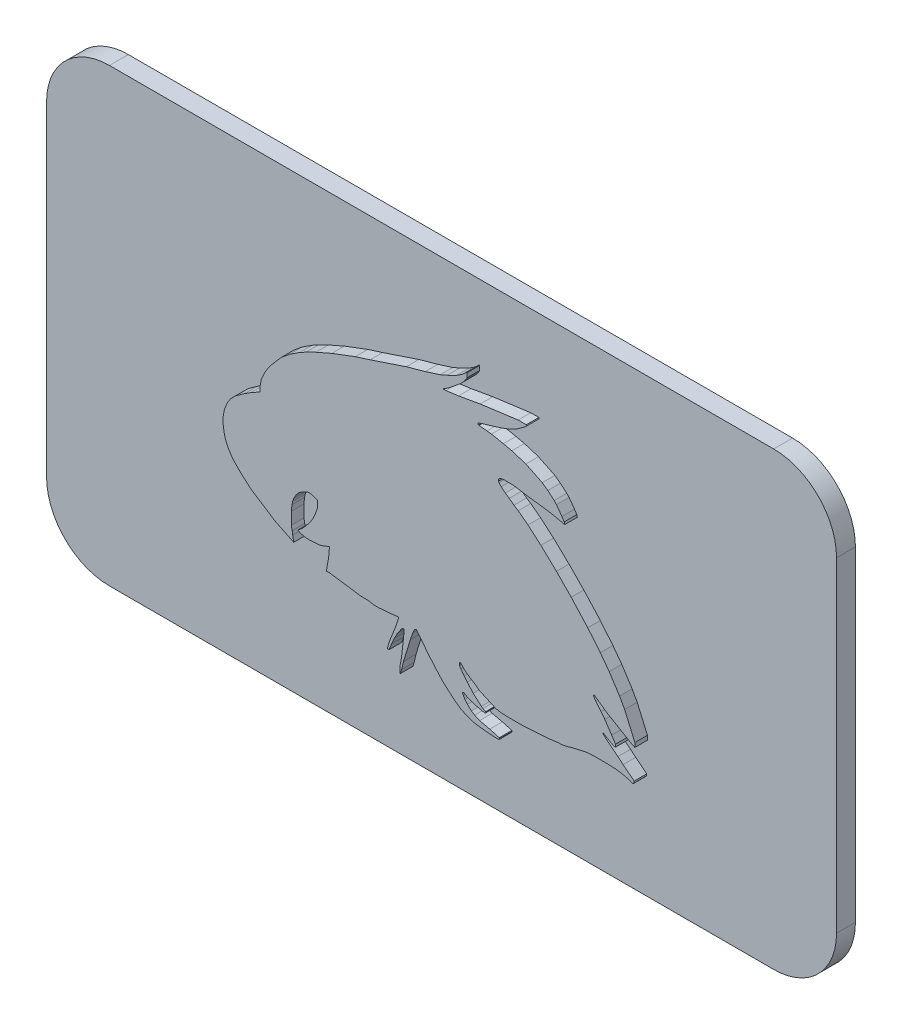
SolidWorks part; units mm, degrees
ref_plane "Alzado" through (0, 0, 0) normal (0, 0, 1) x (1, 0, 0)
ref_plane "Planta" through (0, 0, 0) normal (0, 1, 0) x (1, 0, 0)
ref_plane "Vista lateral" through (0, 0, 0) normal (1, 0, 0) x (0, 0, -1)
sketch "Croquis1" plane through (0, 0, 0) normal (0, 0, 1) x (1, 0, 0)
  line L1 (62.825, -35.85) -> (-62.825, -35.85)
  line L2 (62.825, -35.85) -> (62.825, 35.85)
  line L3 (62.825, 35.85) -> (-62.825, 35.85)
  line L4 (-62.825, -35.85) -> (-62.825, 35.85)
  line L5 (62.825, -35.85) -> (-62.825, 35.85) construction
  line L6 (62.825, 35.85) -> (-62.825, -35.85) construction
  point P0 (0, 0)
  dimension "D1" = 125.65
  dimension "D2" = 71.7
extrude "Saliente-Extruir1" add sketch "Croquis1" along normal blind 3
sketch "Croquis2" plane through (0, 0, 3) normal (0, 0, 1) x (1, 0, 0)
  line L0 (-28.2868, -15.132) -> (26.9333, -15.132) construction
  line L1 (-21.517, -13.1813) -> (-22.2748, -12.8126)
  line L2 (-22.2748, -12.8126) -> (-23.1477, -12.3879)
  line L3 (-23.1477, -12.3879) -> (-24.4405, -11.759)
  line L4 (-24.4405, -11.759) -> (-26.2075, -10.6209)
  line L5 (-26.2075, -10.6209) -> (-28.2313, -9.3174)
  line L6 (-28.2313, -9.3174) -> (-29.9148, -7.8558)
  line L7 (-29.9148, -7.8558) -> (-31.2215, -6.5221)
  line L8 (-31.2215, -6.5221) -> (-31.9463, -5.4019)
  line L9 (-31.9463, -5.4019) -> (-32.4272, -4.3025)
  line L10 (-32.4272, -4.3025) -> (-32.611, -3.4846)
  line L11 (-32.611, -3.4846) -> (-32.7489, -2.4553)
  line L12 (-32.7489, -2.4553) -> (-32.7489, -1.4927)
  line L13 (-32.7489, -1.4927) -> (-32.5191, -0.3183)
  line L14 (-32.5191, -0.3183) -> (-32.0574, 0.7914)
  line L15 (-32.0574, 0.7914) -> (-31.5377, 1.5982)
  line L16 (-31.5377, 1.5982) -> (-30.741, 2.3788)
  line L17 (-30.741, 2.3788) -> (-29.3514, 3.3736)
  line L18 (-29.3514, 3.3736) -> (-28.2983, 4.0551)
  line L19 (-28.2983, 4.0551) -> (-26.9052, 4.8271)
  line L20 (-26.9052, 4.8271) -> (-26.9052, 5.4863)
  line L21 (-26.9052, 5.4863) -> (-26.7928, 6.0605)
  line L22 (-26.7928, 6.0605) -> (-26.6815, 6.6294)
  line L23 (-26.6815, 6.6294) -> (-26.3768, 7.3617)
  line L24 (-26.3768, 7.3617) -> (-26.0101, 8.1154)
  line L25 (-26.0101, 8.1154) -> (-25.6258, 8.7121)
  line L26 (-25.6258, 8.7121) -> (-25.0709, 9.4857)
  line L27 (-25.0709, 9.4857) -> (-24.3658, 10.2978)
  line L28 (-24.3658, 10.2978) -> (-23.91, 10.8228)
  line L29 (-23.91, 10.8228) -> (-23.4854, 11.3118)
  line L30 (-23.4854, 11.3118) -> (-22.749, 11.918)
  line L31 (-22.749, 11.918) -> (-22.1394, 12.4197)
  line L32 (-22.1394, 12.4197) -> (-21.3705, 12.9173)
  line L33 (-21.3705, 12.9173) -> (-20.5919, 13.4211)
  line L34 (-20.5919, 13.4211) -> (-19.5664, 13.9894)
  line L35 (-19.5664, 13.9894) -> (-18.008, 14.7549)
  line L36 (-18.008, 14.7549) -> (-15.4529, 15.8727)
  line L37 (-15.4529, 15.8727) -> (-13.4227, 16.6413)
  line L38 (-13.4227, 16.6413) -> (-11.7288, 17.2826)
  line L39 (-11.7288, 17.2826) -> (-9.3592, 18.0314)
  line L40 (-9.3592, 18.0314) -> (-6.6534, 18.9364)
  line L41 (-6.6534, 18.9364) -> (-3.6082, 19.955)
  line L42 (-3.6082, 19.955) -> (-0.6016, 20.7933)
  line L43 (-0.6016, 20.7933) -> (1.7736, 21.5439)
  line L44 (1.7736, 21.5439) -> (2.8887, 22.0317)
  line L45 (2.8887, 22.0317) -> (4.3568, 22.7528)
  line L46 (4.3568, 22.7528) -> (5.2339, 23.3204)
  line L47 (5.2339, 23.3204) -> (5.6074, 23.6277)
  line L48 (5.6074, 23.6277) -> (5.9069, 23.9212)
  line L49 (5.9069, 23.9212) -> (6.0009, 24.0295)
  line L50 (6.0009, 24.0295) -> (6.0633, 23.9753)
  line L51 (6.0633, 23.9753) -> (6.0633, 23.7745)
  line L52 (6.0633, 23.7745) -> (6.0633, 23.2808)
  line L53 (6.0633, 23.2808) -> (5.9337, 23.0144)
  line L54 (5.9337, 23.0144) -> (5.7055, 22.6964)
  line L55 (5.7055, 22.6964) -> (5.3768, 22.3177)
  line L56 (5.3768, 22.3177) -> (4.9449, 21.8946)
  line L57 (4.9449, 21.8946) -> (4.5718, 21.5875)
  line L58 (4.5718, 21.5875) -> (3.8226, 20.9708)
  line L59 (3.8226, 20.9708) -> (3.3802, 20.6067)
  line L60 (3.3802, 20.6067) -> (2.672, 20.0996)
  line L61 (2.672, 20.0996) -> (2.3312, 19.9322)
  line L62 (2.3312, 19.9322) -> (2.3462, 19.82)
  line L63 (2.3462, 19.82) -> (2.672, 19.82)
  line L64 (2.672, 19.82) -> (3.1872, 19.889)
  line L65 (3.1872, 19.889) -> (3.8931, 19.9836)
  line L66 (3.8931, 19.9836) -> (4.6954, 20.091)
  line L67 (4.6954, 20.091) -> (5.7055, 20.2699)
  line L68 (5.7055, 20.2699) -> (8.1555, 20.7039)
  line L69 (8.1555, 20.7039) -> (11.9262, 21.2089)
  line L70 (11.9262, 21.2089) -> (13.2103, 21.3809)
  line L71 (13.2103, 21.3809) -> (13.6234, 21.4362)
  line L72 (13.6234, 21.4362) -> (14.1773, 21.5104)
  line L73 (14.1773, 21.5104) -> (14.4498, 21.5104)
  line L74 (14.4498, 21.5104) -> (15.4756, 21.5104)
  line L75 (15.4756, 21.5104) -> (15.5606, 21.3916)
  line L76 (15.5606, 21.3916) -> (15.2563, 21.0935)
  line L77 (15.2563, 21.0935) -> (14.8682, 20.8156)
  line L78 (14.8682, 20.8156) -> (14.4709, 20.5312)
  line L79 (14.4709, 20.5312) -> (14.0238, 20.211)
  line L80 (14.0238, 20.211) -> (13.5409, 19.9738)
  line L81 (13.5409, 19.9738) -> (12.4657, 19.4457)
  line L82 (12.4657, 19.4457) -> (11.6404, 19.1332)
  line L83 (11.6404, 19.1332) -> (10.807, 18.8699)
  line L84 (10.807, 18.8699) -> (9.6654, 18.5091)
  line L85 (9.6654, 18.5091) -> (8.1555, 18.0676)
  line L86 (8.1555, 18.0676) -> (7.8519, 17.9526)
  line L87 (7.8519, 17.9526) -> (7.7962, 17.8981)
  line L88 (7.7962, 17.8981) -> (7.7763, 17.7962)
  line L89 (7.7763, 17.7962) -> (7.8128, 17.7589)
  line L90 (7.8128, 17.7589) -> (7.8705, 17.7001)
  line L91 (7.8705, 17.7001) -> (7.959, 17.657)
  line L92 (7.959, 17.657) -> (8.3415, 17.6221)
  line L93 (8.3415, 17.6221) -> (9.2368, 17.5403)
  line L94 (9.2368, 17.5403) -> (9.9299, 17.4501)
  line L95 (9.9299, 17.4501) -> (10.5524, 17.3283)
  line L96 (10.5524, 17.3283) -> (11.0754, 17.226)
  line L97 (11.0754, 17.226) -> (11.8315, 17.078)
  line L98 (11.8315, 17.078) -> (13.174, 16.7719)
  line L99 (13.174, 16.7719) -> (15.4085, 16.0697)
  line L100 (15.4085, 16.0697) -> (16.6832, 15.4495)
  line L101 (16.6832, 15.4495) -> (17.3311, 15.1343)
  line L102 (17.3311, 15.1343) -> (18.0095, 14.8043)
  line L103 (18.0095, 14.8043) -> (18.4689, 14.4748)
  line L104 (18.4689, 14.4748) -> (18.9006, 14.1651)
  line L105 (18.9006, 14.1651) -> (19.3795, 13.7493)
  line L106 (19.3795, 13.7493) -> (19.9071, 13.2912)
  line L107 (19.9071, 13.2912) -> (20.2735, 12.9173)
  line L108 (20.2735, 12.9173) -> (20.6957, 12.3275)
  line L109 (20.6957, 12.3275) -> (21.1404, 11.7065)
  line L110 (21.1404, 11.7065) -> (21.5053, 11.1424)
  line L111 (21.5053, 11.1424) -> (21.5988, 10.8228)
  line L112 (21.5988, 10.8228) -> (21.4848, 10.8228)
  line L113 (21.4848, 10.8228) -> (21.2668, 10.8725)
  line L114 (21.2668, 10.8725) -> (20.7839, 10.9826)
  line L115 (20.7839, 10.9826) -> (20.1856, 11.119)
  line L116 (20.1856, 11.119) -> (19.8101, 11.2046)
  line L117 (19.8101, 11.2046) -> (18.4689, 11.4244)
  line L118 (18.4689, 11.4244) -> (17.1345, 11.5981)
  line L119 (17.1345, 11.5981) -> (15.4085, 11.8227)
  line L120 (15.4085, 11.8227) -> (14.342, 11.9974)
  line L121 (14.342, 11.9974) -> (13.4169, 12.149)
  line L122 (13.4169, 12.149) -> (12.5682, 12.149)
  line L123 (12.5682, 12.149) -> (11.8315, 12.149)
  line L124 (11.8315, 12.149) -> (11.4534, 12.0984)
  line L125 (11.4534, 12.0984) -> (11.2452, 11.9636)
  line L126 (11.2452, 11.9636) -> (11.0273, 11.8227)
  line L127 (11.0273, 11.8227) -> (11.0273, 11.5112)
  line L128 (11.0273, 11.5112) -> (11.1362, 11.3429)
  line L129 (11.1362, 11.3429) -> (11.4892, 10.9826)
  line L130 (11.4892, 10.9826) -> (12.1333, 10.4234)
  line L131 (12.1333, 10.4234) -> (12.7615, 10.0188)
  line L132 (12.7615, 10.0188) -> (13.5227, 9.4452)
  line L133 (13.5227, 9.4452) -> (14.1773, 9.0237)
  line L134 (14.1773, 9.0237) -> (15.0866, 8.3385)
  line L135 (15.0866, 8.3385) -> (15.7442, 7.8431)
  line L136 (15.7442, 7.8431) -> (16.765, 6.9569)
  line L137 (16.765, 6.9569) -> (17.7974, 6.0605)
  line L138 (17.7974, 6.0605) -> (20.2735, 3.7144)
  line L139 (20.2735, 3.7144) -> (22.6165, 1.3228)
  line L140 (22.6165, 1.3228) -> (24.108, -0.3183)
  line L141 (24.108, -0.3183) -> (25.2477, -1.5724)
  line L142 (25.2477, -1.5724) -> (27.2505, -4.0055)
  line L143 (27.2505, -4.0055) -> (28.6624, -5.8995)
  line L144 (28.6624, -5.8995) -> (29.5473, -7.2671)
  line L145 (29.5473, -7.2671) -> (30.3099, -8.4457)
  line L146 (30.3099, -8.4457) -> (31.1165, -9.9011)
  line L147 (31.1165, -9.9011) -> (31.5758, -10.951)
  line L148 (31.5758, -10.951) -> (32.0048, -11.9316)
  line L149 (32.0048, -11.9316) -> (32.3463, -12.7124)
  line L150 (32.3463, -12.7124) -> (32.749, -13.6328)
  line L151 (32.749, -13.6328) -> (32.749, -14.3072)
  line L152 (32.749, -14.3072) -> (32.1756, -14.0282)
  line L153 (32.1756, -14.0282) -> (28.2991, -11.759)
  line L154 (28.2991, -11.759) -> (26.2491, -10.2885)
  line L155 (26.2491, -10.2885) -> (26.1504, -10.426)
  line L156 (26.1504, -10.426) -> (26.2357, -10.6209)
  line L157 (26.2357, -10.6209) -> (26.536, -11.0238)
  line L158 (26.536, -11.0238) -> (27.3685, -12.0352)
  line L159 (27.3685, -12.0352) -> (27.9564, -12.8239)
  line L160 (27.9564, -12.8239) -> (29.0526, -14.4519)
  line L161 (29.0526, -14.4519) -> (29.664, -15.3967)
  line L162 (29.664, -15.3967) -> (29.664, -15.5345)
  line L163 (29.664, -15.5345) -> (29.664, -15.8152)
  line L164 (29.664, -15.8152) -> (29.5151, -15.8152)
  line L165 (29.5151, -15.8152) -> (29.2885, -15.778)
  line L166 (29.2885, -15.778) -> (29.1049, -15.6463)
  line L167 (29.1049, -15.6463) -> (28.6521, -15.3813)
  line L168 (28.6521, -15.3813) -> (28.0759, -15.044)
  line L169 (28.0759, -15.044) -> (27.7627, -14.8606)
  line L170 (27.7627, -14.8606) -> (27.6625, -14.8606)
  line L171 (27.6625, -14.8606) -> (27.6625, -14.9523)
  line L172 (27.6625, -14.9523) -> (27.7627, -15.0242)
  line L173 (27.7627, -15.0242) -> (28.0852, -15.3533)
  line L174 (28.0852, -15.3533) -> (29.2528, -16.2787)
  line L175 (29.2528, -16.2787) -> (30.05, -16.9106)
  line L176 (30.05, -16.9106) -> (30.871, -17.6025)
  line L177 (30.871, -17.6025) -> (32.6352, -19.0007)
  line L178 (32.6352, -19.0007) -> (32.6352, -19.1399)
  line L179 (32.6352, -19.1399) -> (32.6352, -19.268)
  line L180 (32.6352, -19.268) -> (32.5747, -19.3397)
  line L181 (32.5747, -19.3397) -> (32.4354, -19.4299)
  line L182 (32.4354, -19.4299) -> (32.203, -19.3769)
  line L183 (32.203, -19.3769) -> (31.7079, -19.204)
  line L184 (31.7079, -19.204) -> (31.0816, -19.0258)
  line L185 (31.0816, -19.0258) -> (29.7309, -18.8045)
  line L186 (29.7309, -18.8045) -> (28.364, -18.7418)
  line L187 (28.364, -18.7418) -> (26.8844, -18.7418)
  line L188 (26.8844, -18.7418) -> (26.0627, -18.7418)
  line L189 (26.0627, -18.7418) -> (25.0913, -18.8045)
  line L190 (25.0913, -18.8045) -> (24.1584, -19.0141)
  line L191 (24.1584, -19.0141) -> (23.2084, -19.2276)
  line L192 (23.2084, -19.2276) -> (22.7096, -19.3397)
  line L193 (22.7096, -19.3397) -> (22.4527, -19.4149)
  line L194 (22.4527, -19.4149) -> (22.3674, -19.47)
  line L195 (22.3674, -19.47) -> (21.3136, -19.7068)
  line L196 (21.3136, -19.7068) -> (20.2735, -19.774)
  line L197 (20.2735, -19.774) -> (19.0844, -19.952)
  line L198 (19.0844, -19.952) -> (17.4104, -20.06)
  line L199 (17.4104, -20.06) -> (16.2997, -20.1317)
  line L200 (16.2997, -20.1317) -> (15.5606, -20.1794)
  line L201 (15.5606, -20.1794) -> (15.0169, -20.2145)
  line L202 (15.0169, -20.2145) -> (13.8361, -20.2145)
  line L203 (13.8361, -20.2145) -> (12.5682, -20.2145)
  line L204 (12.5682, -20.2145) -> (11.4892, -20.165)
  line L205 (11.4892, -20.165) -> (10.6698, -20.0307)
  line L206 (10.6698, -20.0307) -> (7.959, -18.8045)
  line L207 (7.959, -18.8045) -> (7.3545, -18.3254)
  line L208 (7.3545, -18.3254) -> (6.5416, -17.8228)
  line L209 (6.5416, -17.8228) -> (5.6267, -17.157)
  line L210 (5.6267, -17.157) -> (5.1526, -16.6264)
  line L211 (5.1526, -16.6264) -> (5.0145, -16.4719)
  line L212 (5.0145, -16.4719) -> (4.8949, -16.5321)
  line L213 (4.8949, -16.5321) -> (4.8091, -16.7219)
  line L214 (4.8091, -16.7219) -> (4.8464, -16.9715)
  line L215 (4.8464, -16.9715) -> (5.0708, -17.3183)
  line L216 (5.0708, -17.3183) -> (5.576, -18.0049)
  line L217 (5.576, -18.0049) -> (6.0841, -18.6506)
  line L218 (6.0841, -18.6506) -> (6.6499, -19.2837)
  line L219 (6.6499, -19.2837) -> (7.028, -19.7068)
  line L220 (7.028, -19.7068) -> (7.7763, -20.3599)
  line L221 (7.7763, -20.3599) -> (8.3415, -20.8531)
  line L222 (8.3415, -20.8531) -> (8.5849, -21.0303)
  line L223 (8.5849, -21.0303) -> (8.8939, -21.191)
  line L224 (8.8939, -21.191) -> (9.0104, -21.2516)
  line L225 (9.0104, -21.2516) -> (9.055, -21.3401)
  line L226 (9.055, -21.3401) -> (9.012, -21.4227)
  line L227 (9.012, -21.4227) -> (8.8939, -21.4822)
  line L228 (8.8939, -21.4822) -> (8.7394, -21.4569)
  line L229 (8.7394, -21.4569) -> (8.4451, -21.4086)
  line L230 (8.4451, -21.4086) -> (8.0838, -21.3263)
  line L231 (8.0838, -21.3263) -> (7.6236, -21.2213)
  line L232 (7.6236, -21.2213) -> (7.1015, -21.0728)
  line L233 (7.1015, -21.0728) -> (6.5206, -20.8699)
  line L234 (6.5206, -20.8699) -> (6.1223, -20.6898)
  line L235 (6.1223, -20.6898) -> (5.83, -20.5377)
  line L236 (5.83, -20.5377) -> (5.6074, -20.4001)
  line L237 (5.6074, -20.4001) -> (5.4986, -20.3753)
  line L238 (5.4986, -20.3753) -> (5.4158, -20.3877)
  line L239 (5.4158, -20.3877) -> (5.3648, -20.4134)
  line L240 (5.3648, -20.4134) -> (5.3465, -20.4935)
  line L241 (5.3465, -20.4935) -> (5.3465, -20.5653)
  line L242 (5.3465, -20.5653) -> (5.3903, -20.6523)
  line L243 (5.3903, -20.6523) -> (5.4769, -20.8242)
  line L244 (5.4769, -20.8242) -> (5.7187, -21.1979)
  line L245 (5.7187, -21.1979) -> (6.1223, -21.6832)
  line L246 (6.1223, -21.6832) -> (6.7576, -22.2819)
  line L247 (6.7576, -22.2819) -> (7.2768, -22.6029)
  line L248 (7.2768, -22.6029) -> (8.0589, -22.9567)
  line L249 (8.0589, -22.9567) -> (8.8527, -23.1377)
  line L250 (8.8527, -23.1377) -> (9.6654, -23.323)
  line L251 (9.6654, -23.323) -> (10.3038, -23.5046)
  line L252 (10.3038, -23.5046) -> (10.9527, -23.6892)
  line L253 (10.9527, -23.6892) -> (11.1761, -23.7527)
  line L254 (11.1761, -23.7527) -> (11.2313, -23.8623)
  line L255 (11.2313, -23.8623) -> (11.2037, -23.9594)
  line L256 (11.2037, -23.9594) -> (11.0644, -24.0296)
  line L257 (11.0644, -24.0296) -> (10.8993, -24.0296)
  line L258 (10.8993, -24.0296) -> (10.4352, -24.0296)
  line L259 (10.4352, -24.0296) -> (9.6101, -23.9761)
  line L260 (9.6101, -23.9761) -> (7.9403, -23.8075)
  line L261 (7.9403, -23.8075) -> (7.2181, -23.6892)
  line L262 (7.2181, -23.6892) -> (6.3917, -23.4541)
  line L263 (6.3917, -23.4541) -> (5.0708, -22.8566)
  line L264 (5.0708, -22.8566) -> (3.8931, -21.9994)
  line L265 (3.8931, -21.9994) -> (2.7147, -20.971)
  line L266 (2.7147, -20.971) -> (2.0296, -20.3253)
  line L267 (2.0296, -20.3253) -> (1.1626, -19.3552)
  line L268 (1.1626, -19.3552) -> (-0.0169, -17.9806)
  line L269 (-0.0169, -17.9806) -> (-1.0822, -16.627)
  line L270 (-1.0822, -16.627) -> (-1.721, -15.8152)
  line L271 (-1.721, -15.8152) -> (-2.0213, -15.4652)
  line L272 (-2.0213, -15.4652) -> (-2.1491, -15.4652)
  line L273 (-2.1491, -15.4652) -> (-2.2299, -15.5345)
  line L274 (-2.2299, -15.5345) -> (-2.3599, -15.7132)
  line L275 (-2.3599, -15.7132) -> (-2.5715, -16.181)
  line L276 (-2.5715, -16.181) -> (-2.9637, -17.3038)
  line L277 (-2.9637, -17.3038) -> (-3.7526, -19.863)
  line L278 (-3.7526, -19.863) -> (-4.0708, -20.8952)
  line L279 (-4.0708, -20.8952) -> (-4.3526, -22.131)
  line L280 (-4.3526, -22.131) -> (-4.5526, -22.7798)
  line L281 (-4.5526, -22.7798) -> (-4.6449, -22.7798)
  line L282 (-4.6449, -22.7798) -> (-4.6449, -22.6982)
  line L283 (-4.6449, -22.6982) -> (-4.6449, -22.4554)
  line L284 (-4.6449, -22.4554) -> (-4.5935, -21.6619)
  line L285 (-4.5935, -21.6619) -> (-4.4068, -20.6898)
  line L286 (-4.4068, -20.6898) -> (-4.333, -20.0978)
  line L287 (-4.333, -20.0978) -> (-4.2117, -19.0258)
  line L288 (-4.2117, -19.0258) -> (-4.1166, -18.1857)
  line L289 (-4.1166, -18.1857) -> (-4.0085, -17.1149)
  line L290 (-4.0085, -17.1149) -> (-3.9732, -16.5695)
  line L291 (-3.9732, -16.5695) -> (-3.9865, -16.4804)
  line L292 (-3.9865, -16.4804) -> (-4.016, -16.3797)
  line L293 (-4.016, -16.3797) -> (-4.0989, -16.3541)
  line L294 (-4.0989, -16.3541) -> (-4.1863, -16.3797)
  line L295 (-4.1863, -16.3797) -> (-4.2618, -16.4445)
  line L296 (-4.2618, -16.4445) -> (-4.4068, -16.5689)
  line L297 (-4.4068, -16.5689) -> (-4.7011, -17.045)
  line L298 (-4.7011, -17.045) -> (-5.0368, -17.5062)
  line L299 (-5.0368, -17.5062) -> (-5.4977, -18.3924)
  line L300 (-5.4977, -18.3924) -> (-5.953, -19.3989)
  line L301 (-5.953, -19.3989) -> (-6.1988, -20.006)
  line L302 (-6.1988, -20.006) -> (-6.3558, -20.3938)
  line L303 (-6.3558, -20.3938) -> (-6.4317, -20.3938)
  line L304 (-6.4317, -20.3938) -> (-6.5533, -20.3938)
  line L305 (-6.5533, -20.3938) -> (-6.5857, -20.3007)
  line L306 (-6.5857, -20.3007) -> (-6.6008, -20.1999)
  line L307 (-6.6008, -20.1999) -> (-6.5695, -20.1226)
  line L308 (-6.5695, -20.1226) -> (-6.5367, -20.0161)
  line L309 (-6.5367, -20.0161) -> (-6.252, -19.0925)
  line L310 (-6.252, -19.0925) -> (-5.9881, -18.4407)
  line L311 (-5.9881, -18.4407) -> (-5.7409, -17.81)
  line L312 (-5.7409, -17.81) -> (-5.5125, -17.2457)
  line L313 (-5.5125, -17.2457) -> (-5.2053, -16.43)
  line L314 (-5.2053, -16.43) -> (-4.9989, -15.7605)
  line L315 (-4.9989, -15.7605) -> (-4.7995, -15.1139)
  line L322 (-4.7995, -15.1139) -> (-5.6267, -15.2378)
  line L323 (-5.6267, -15.2378) -> (-7.9672, -15.4372)
  line L324 (-7.9672, -15.4372) -> (-8.7481, -15.4372)
  line L325 (-8.7481, -15.4372) -> (-9.6736, -15.2595)
  line L326 (-9.6736, -15.2595) -> (-10.8837, -15.2595)
  line L327 (-10.8837, -15.2595) -> (-12.948, -14.9523)
  line L328 (-12.948, -14.9523) -> (-14.4421, -14.73)
  line L329 (-14.4421, -14.73) -> (-15.6798, -14.5458)
  line L330 (-15.6798, -14.5458) -> (-16.3131, -14.5458)
  line L331 (-16.3131, -14.5458) -> (-16.1994, -13.7819)
  line L332 (-16.1994, -13.7819) -> (-15.9709, -12.5919)
  line L333 (-15.9709, -12.5919) -> (-15.9004, -11.759)
  line L334 (-15.9004, -11.759) -> (-15.8321, -10.951)
  line L335 (-15.8321, -10.951) -> (-16.0852, -11.0238)
  line L336 (-16.0852, -11.0238) -> (-16.6779, -11.2863)
  line L337 (-16.6779, -11.2863) -> (-17.4329, -11.5034)
  line L338 (-17.4329, -11.5034) -> (-18.1747, -11.5666)
  line L339 (-18.1747, -11.5666) -> (-18.8661, -11.5994)
  line L340 (-18.8661, -11.5994) -> (-19.4838, -11.5994)
  line L341 (-19.4838, -11.5994) -> (-20.0496, -11.4907)
  line L342 (-20.0496, -11.4907) -> (-20.4649, -11.3684)
  line L343 (-20.4649, -11.3684) -> (-20.7635, -11.2384)
  line L344 (-20.7635, -11.2384) -> (-20.8216, -11.1527)
  line L345 (-20.8216, -11.1527) -> (-20.7635, -11.0642)
  line L346 (-20.7635, -11.0642) -> (-20.656, -10.9914)
  line L347 (-20.656, -10.9914) -> (-20.5183, -10.8981)
  line L348 (-20.5183, -10.8981) -> (-20.0952, -10.519)
  line L349 (-20.0952, -10.519) -> (-19.7136, -10.0975)
  line L350 (-19.7136, -10.0975) -> (-19.3096, -9.6141)
  line L351 (-19.3096, -9.6141) -> (-18.9361, -9.1346)
  line L352 (-18.9361, -9.1346) -> (-18.5188, -8.4987)
  line L353 (-18.5188, -8.4987) -> (-18.1465, -7.7168)
  line L354 (-18.1465, -7.7168) -> (-17.8698, -6.9576)
  line L355 (-17.8698, -6.9576) -> (-17.7549, -6.5677)
  line L356 (-17.7549, -6.5677) -> (-17.7549, -5.4804)
  line L357 (-17.7549, -5.4804) -> (-18.0765, -5.3856)
  line L358 (-18.0765, -5.3856) -> (-18.3516, -5.2854)
  line L359 (-18.3516, -5.2854) -> (-18.7275, -5.1484)
  line L360 (-18.7275, -5.1484) -> (-19.1881, -5.1484)
  line L361 (-19.1881, -5.1484) -> (-19.5116, -5.2169)
  line L362 (-19.5116, -5.2169) -> (-20.2452, -5.6003)
  line L363 (-20.2452, -5.6003) -> (-20.7635, -6.0033)
  line L364 (-20.7635, -6.0033) -> (-21.1435, -6.458)
  line L365 (-21.1435, -6.458) -> (-21.4956, -7.1084)
  line L366 (-21.4956, -7.1084) -> (-21.6853, -7.6288)
  line L367 (-21.6853, -7.6288) -> (-21.7859, -8.1334)
  line L368 (-21.7859, -8.1334) -> (-21.9006, -9.0969)
  line L369 (-21.9006, -9.0969) -> (-21.9006, -10.0975)
  line L370 (-21.9006, -10.0975) -> (-21.9006, -10.7086)
  line L371 (-21.9006, -10.7086) -> (-21.9006, -11.0278)
  line L372 (-21.9006, -11.0278) -> (-21.7566, -11.7079)
  line L373 (-21.7566, -11.7079) -> (-21.6853, -12.2584)
  line L374 (-21.6853, -12.2584) -> (-21.517, -13.1813)
extrude "Saliente-Extruir2" add sketch "Croquis2" along normal blind 2
fillet "Redondeo1" radius 10 4 edges at (-62.825, 35.85, 1.5) (-62.825, -35.85, 1.5) (62.825, -35.85, 1.5) (62.825, 35.85, 1.5)
